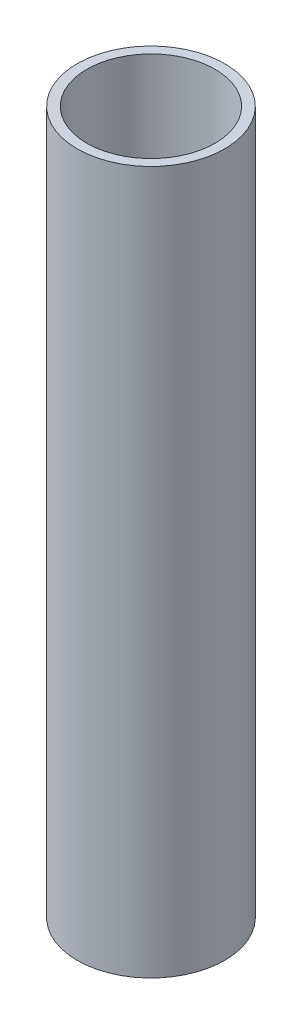
SolidWorks part; units mm, degrees
ref_plane "Front Plane" through (0, 0, 0) normal (0, 0, 1) x (1, 0, 0)
ref_plane "Top Plane" through (0, 0, 0) normal (0, 1, 0) x (1, 0, 0)
ref_plane "Right Plane" through (0, 0, 0) normal (1, 0, 0) x (0, 0, -1)
sketch "Sketch1" plane through (0, 0, 0) normal (0, 1, 0) x (1, 0, 0)
  circle A0 centre (0, 0) radius 16.8
  circle A1 centre (0, 0) radius 14.6
  dimension "D1" = 33.6
  dimension "D2" = 29.2
extrude "Boss-Extrude1" add sketch "Sketch1" along normal blind 160
